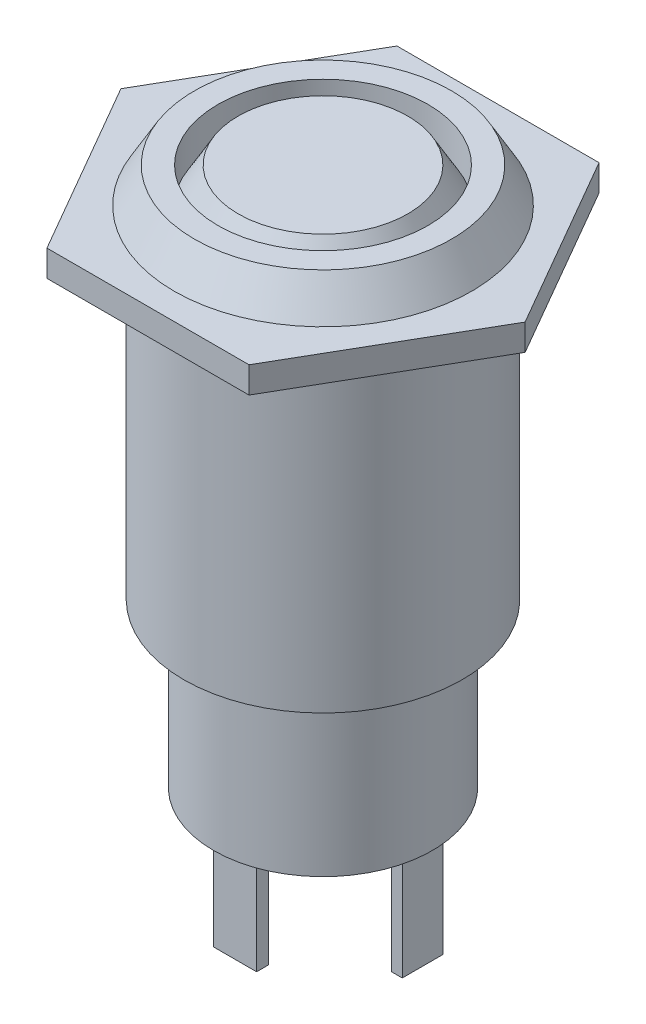
SolidWorks part; units mm, degrees
ref_plane "Front Plane" through (0, 0, 0) normal (0, 0, 1) x (1, 0, 0)
ref_plane "Top Plane" through (0, 0, 0) normal (0, 1, 0) x (1, 0, 0)
ref_plane "Right Plane" through (0, 0, 0) normal (1, 0, 0) x (0, 0, -1)
sketch "Sketch1" plane through (0, 0, 0) normal (0, 1, 0) x (1, 0, 0)
  circle A0 centre (0, 0) radius 7.95
  dimension "D1" = 15.9
extrude "Boss-Extrude1" add sketch "Sketch1" along normal blind 19.5
sketch "Sketch2" plane through (0, 19.5, 0) normal (0, 1, 0) x (1, 0, 0)
  line L1 (11.547, 0) -> (5.7735, 10)
  line L2 (5.7735, 10) -> (-5.7735, 10)
  line L3 (-5.7735, 10) -> (-11.547, 0)
  line L4 (-11.547, 0) -> (-5.7735, -10)
  line L5 (-5.7735, -10) -> (5.7735, -10)
  line L6 (5.7735, -10) -> (11.547, 0)
  circle A0 centre (0, 0) radius 10 construction
  dimension "D1" = 20
extrude "Boss-Extrude2" add sketch "Sketch2" against normal blind 1.5
sketch "Sketch3" plane through (0, 19.5, 0) normal (0, 1, 0) x (1, 0, 0)
  circle A0 centre (0, 0) radius 8.5
  dimension "D1" = 17
extrude "Boss-Extrude3" add sketch "Sketch3" along normal blind 2 draft 30
sketch "Sketch4" plane through (0, 21.5, 0) normal (0, 1, 0) x (1, 0, 0)
  circle A0 centre (0, 0) radius 6
extrude "Cut-Extrude1" cut sketch "Sketch4" against normal blind 2
sketch "Sketch6" plane through (0, 19.5, 0) normal (0, 1, 0) x (1, 0, 0)
  circle A1 centre (0, 0) radius 6
  circle A2 centre (0, 0) radius 6
  dimension "D1" = 0
extrude "Boss-Extrude4" add sketch "Sketch6" along normal blind 2 draft 30
sketch "Sketch7" plane through (0, 0, 0) normal (0, -1, 0) x (1, 0, 0)
  circle A0 centre (0, 0) radius 6.25
  dimension "D1" = 12.5
extrude "Boss-Extrude5" add sketch "Sketch7" along normal blind 9.3
sketch "Sketch8" plane through (0, -9.3, 0) normal (0, -1, 0) x (1, 0, 0)
  line L0 (0, 0) -> (0, 6.25) construction
  line L1 (0, 6.25) -> (6.25, 0) construction
  line L2 (6.25, 0) -> (0, -6.25) construction
  line L3 (0, -6.25) -> (0, 0) construction
  line L5 (-1.228, 4.3459) -> (1.228, 4.3459)
  line L6 (-1.228, 4.3459) -> (-1.228, 5.022)
  line L7 (-1.228, 5.022) -> (1.228, 5.022)
  line L8 (1.228, 4.3459) -> (1.228, 5.022)
  line L9 (-1.228, 4.3459) -> (1.228, 5.022) construction
  line L10 (-1.228, 5.022) -> (1.228, 4.3459) construction
  line L11 (5.6961, 1.1669) -> (5.0831, 1.1669)
  line L12 (5.6961, 1.1669) -> (5.6961, -1.1669)
  line L13 (5.6961, -1.1669) -> (5.0831, -1.1669)
  line L14 (5.0831, 1.1669) -> (5.0831, -1.1669)
  line L15 (5.6961, 1.1669) -> (5.0831, -1.1669) construction
  line L16 (5.6961, -1.1669) -> (5.0831, 1.1669) construction
  line L17 (-1.228, -5.3899) -> (1.228, -5.3899)
  line L18 (-1.228, -5.3899) -> (-1.228, -4.5756)
  line L19 (-1.228, -4.5756) -> (1.228, -4.5756)
  line L20 (1.228, -5.3899) -> (1.228, -4.5756)
  line L21 (-1.228, -5.3899) -> (1.228, -4.5756) construction
  line L22 (-1.228, -4.5756) -> (1.228, -5.3899) construction
  line L23 (-5.0091, -1.1669) -> (-4.4063, -1.1669)
  line L24 (-5.0091, -1.1669) -> (-5.0091, 1.1669)
  line L25 (-5.0091, 1.1669) -> (-4.4063, 1.1669)
  line L26 (-4.4063, -1.1669) -> (-4.4063, 1.1669)
  line L27 (-5.0091, -1.1669) -> (-4.4063, 1.1669) construction
  line L28 (-5.0091, 1.1669) -> (-4.4063, -1.1669) construction
  circle A0 centre (0, 0) radius 6.25 construction
  circle A1 centre (0, 0) radius 6.25 construction
  point P7 (0, 4.6839)
  point P14 (5.3896, 0)
  point P19 (0, -4.9827)
  point P24 (-4.7077, 0)
extrude "Boss-Extrude6" add sketch "Sketch8" along normal blind 6
